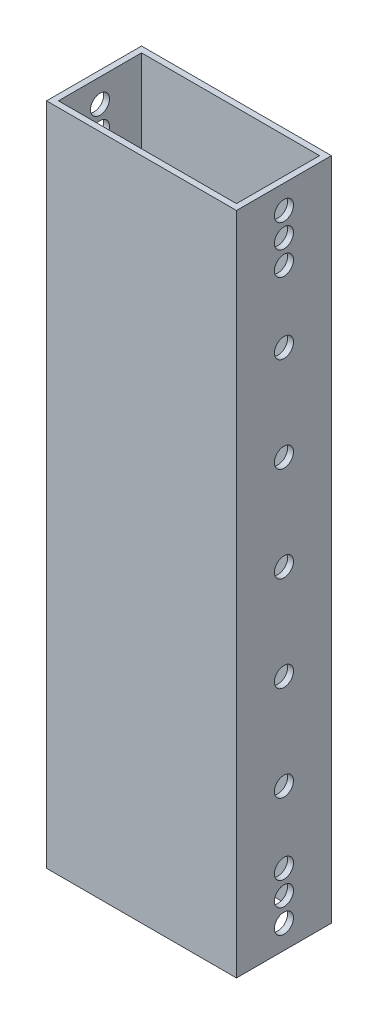
SolidWorks part; units mm, degrees
ref_plane "Front Plane" through (0, 0, 0) normal (0, 0, 1) x (1, 0, 0)
ref_plane "Top Plane" through (0, 0, 0) normal (0, 1, 0) x (1, 0, 0)
ref_plane "Right Plane" through (0, 0, 0) normal (1, 0, 0) x (0, 0, -1)
sketch "Sketch2" plane through (0, 0, 0) normal (0, 1, 0) x (1, 0, 0)
  line L1 (0, 0) -> (50.8, 0)
  line L2 (0, 0) -> (0, 25.4)
  line L3 (0, 25.4) -> (50.8, 25.4)
  line L4 (50.8, 0) -> (50.8, 25.4)
  line L5 (1.5875, 1.5875) -> (49.2125, 1.5875)
  line L6 (1.5875, 1.5875) -> (1.5875, 23.8125)
  line L7 (1.5875, 23.8125) -> (49.2125, 23.8125)
  line L8 (49.2125, 1.5875) -> (49.2125, 23.8125)
  dimension "D1" = 50.8
  dimension "D2" = 25.4
  dimension "D3" = 1.5875
  dimension "D4" = 1.5875
  dimension "D5" = 1.5875
  dimension "D6" = 1.5875
extrude "Boss-Extrude2" add sketch "Sketch2" along normal blind 177.8
sketch "Sketch4" plane through (0, 0, 0) normal (-1, 0, 0) x (0, 0, 1)
  line L0 (0, 177.8) -> (0, 0) construction
  line L1 (-25.4, 177.8) -> (0, 177.8) construction
  circle A0 centre (-12.7, 171.45) radius 2.5527
  dimension "D1" = 5.1054
  dimension "D2" = 12.7
  dimension "D3" = 6.35
extrude "Cut-Extrude2" cut sketch "Sketch4" against normal blind 50.8
pattern_linear "LPattern1" count 27 spacing 6.35 along (0, -1, 0) skipping (3, 0), (4, 0), (5, 0), (6, 0), (7, 0), (8, 0), (9, 0), (10, 0), (11, 0), (12, 0), (13, 0), (14, 0), (15, 0), (16, 0), (17, 0), (18, 0), (19, 0), (20, 0), (21, 0), (22, 0), (23, 0) of "Cut-Extrude2"
sketch "Sketch5" plane through (0, 0, 0) normal (-1, 0, 0) x (0, 0, 1)
  line L0 (0, 177.8) -> (0, 0) construction
  line L1 (-25.4, 177.8) -> (0, 177.8) construction
  circle A0 centre (-12.7, 139.7) radius 2.5527
  dimension "D1" = 5.1054
  dimension "D2" = 12.7
  dimension "D3" = 38.1
extrude "Cut-Extrude3" cut sketch "Sketch5" against normal blind 50.8
pattern_linear "LPattern2" count 5 spacing 25.4 along (0, -1, 0) of "Cut-Extrude3"
